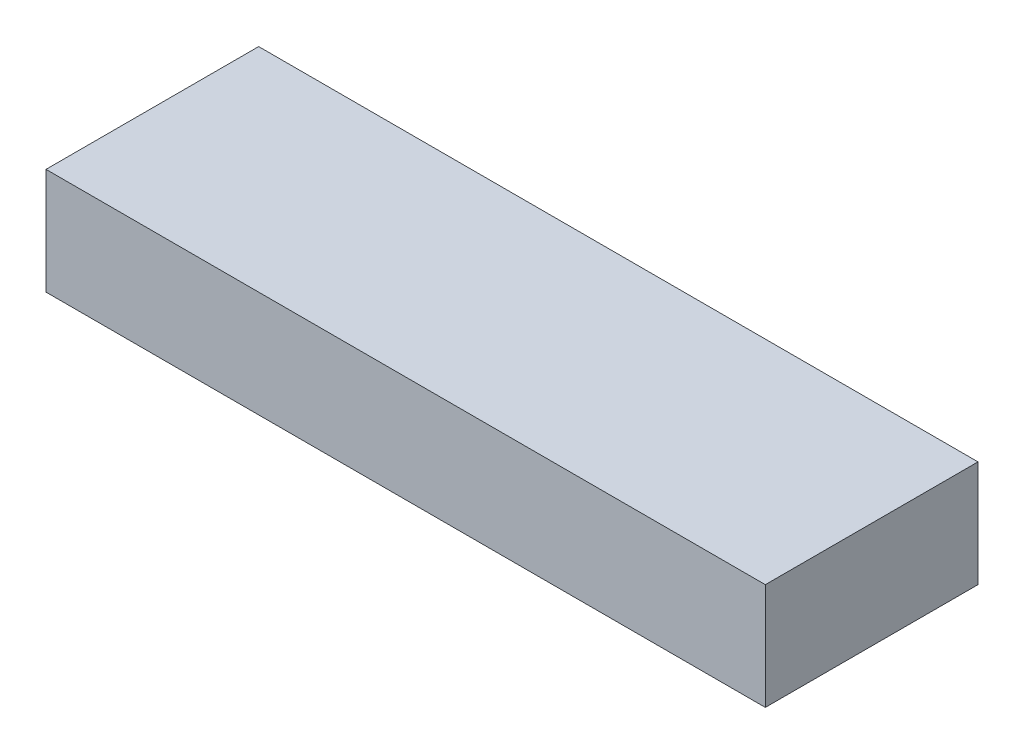
SolidWorks part; units mm, degrees
ref_plane "Front Plane" through (0, 0, 0) normal (0, 0, 1) x (1, 0, 0)
ref_plane "Top Plane" through (0, 0, 0) normal (0, 1, 0) x (1, 0, 0)
ref_plane "Right Plane" through (0, 0, 0) normal (1, 0, 0) x (0, 0, -1)
sketch "Sketch1" plane through (0, 0, 0) normal (0, 1, 0) x (1, 0, 0)
  line L1 (-73.025, -21.59) -> (73.025, -21.59)
  line L2 (-73.025, -21.59) -> (-73.025, 21.59)
  line L3 (-73.025, 21.59) -> (73.025, 21.59)
  line L4 (73.025, -21.59) -> (73.025, 21.59)
  line L5 (-73.025, -21.59) -> (73.025, 21.59) construction
  line L6 (-73.025, 21.59) -> (73.025, -21.59) construction
  point P0 (0, 0)
  dimension "D1" = 43.18
  dimension "D2" = 146.05
extrude "Boss-Extrude1" add sketch "Sketch1" along normal blind 21.59
